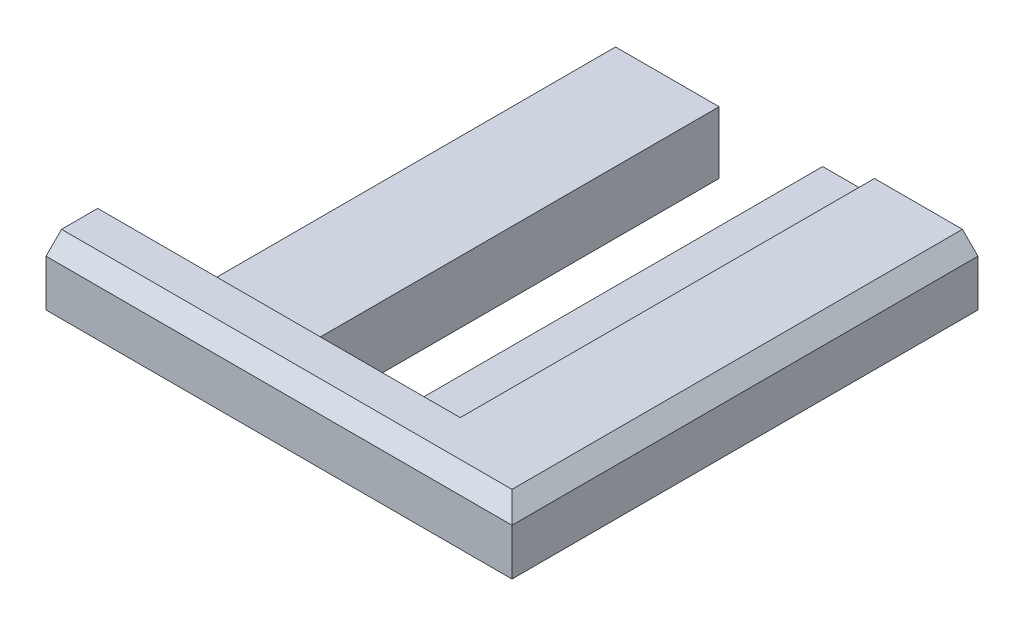
SolidWorks part; units mm, degrees
ref_plane "Front Plane" through (0, 0, 0) normal (0, 0, 1) x (1, 0, 0)
ref_plane "Top Plane" through (0, 0, 0) normal (0, 1, 0) x (1, 0, 0)
ref_plane "Right Plane" through (0, 0, 0) normal (1, 0, 0) x (0, 0, -1)
sketch "Sketch1" plane through (0, 0, 0) normal (0, 1, 0) x (1, 0, 0)
  line L0 (-25.4, 25.4) -> (-228.6, 25.4)
  line L1 (0, 0) -> (-228.6, 0)
  line L2 (0, 0) -> (0, 228.6)
  line L3 (0, 228.6) -> (-228.6, 228.6)
  line L4 (-228.6, 0) -> (-228.6, 228.6)
  line L5 (-25.4, 25.4) -> (-25.4, 228.6)
  line L6 (-76.2, 25.4) -> (-76.2, 228.6)
  line L7 (-127, 25.4) -> (-127, 228.6)
  line L8 (-177.8, 25.4) -> (-177.8, 228.6)
  dimension "D1" = 228.6
  dimension "D2" = 228.6
  dimension "D3" = 25.4
  dimension "D4" = 50.8
  dimension "D5" = 50.8
  dimension "D6" = 50.8
extrude "Boss-Extrude1" add sketch "Sketch1" along normal blind 38.1 contours L5 L0 L4 L1 L2 L3 | L6 L0 L5 L3 | L8 L0 L7 L3
sketch "Sketch3" plane through (-228.6, 0, 0) normal (-1, 0, 0) x (0, 0, 1)
  circle A0 centre (-12.7, 19.05) radius 9.525
  dimension "D1" = 19.05
extrude "Cut-Extrude1" cut sketch "Sketch3" against normal blind 38.1
sketch "Sketch4" plane through (0, 0, -228.6) normal (0, 0, -1) x (-1, 0, 0)
  circle A0 centre (12.6849, 19.05) radius 9.525
  dimension "D1" = 19.05
extrude "Cut-Extrude2" cut sketch "Sketch4" against normal blind 38.1
sketch "Sketch5" plane through (0, 38.1, 0) normal (0, 1, 0) x (1, 0, 0)
  line L0 (-50.8, 25.4) -> (-279.4, 25.371)
  line L2 (-50.8, 25.4) -> (-50.8, 279.4)
  line L3 (-228.6, 25.371) -> (-330.2, 25.371) construction
  line L4 (-279.4, 25.371) -> (-279.4, 279.4)
  line L5 (-279.4, 279.4) -> (-50.8, 279.4)
extrude "Cut-Extrude3" cut sketch "Sketch5" against normal blind 7.62
chamfer "Chamfer1" distance 7.62 angle 45 4 edges at (-114.3, 0, 0) (-114.3, 38.1, 0) (0, 0, -114.3) (0, 38.1, -114.3)
